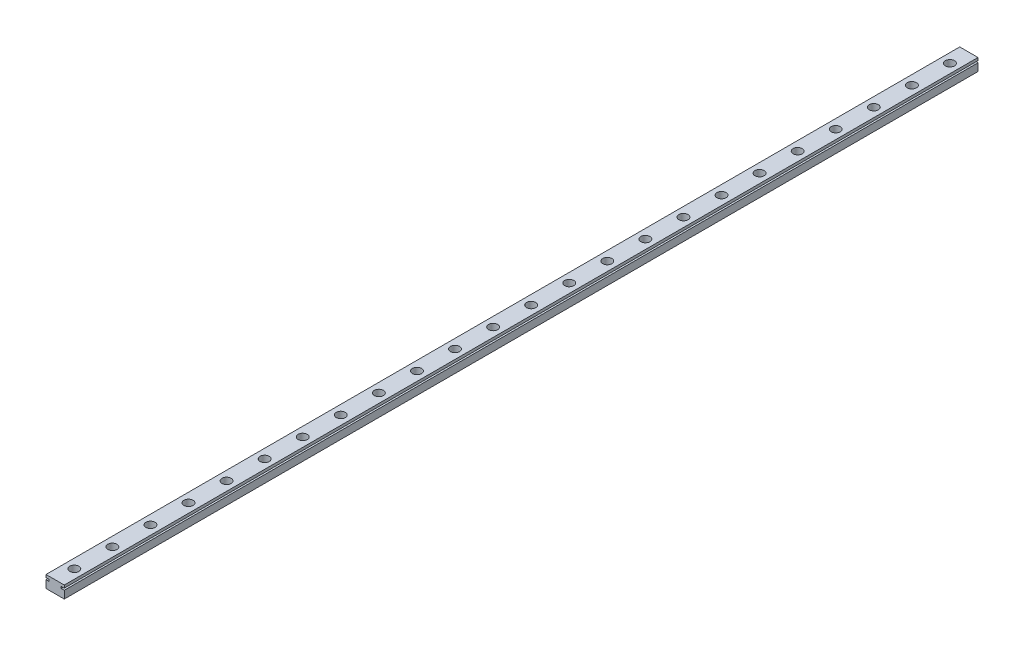
SolidWorks part; units mm, degrees
ref_plane "Plan de face" through (0, 0, 0) normal (0, 0, 1) x (1, 0, 0)
ref_plane "Plan de dessus" through (0, 0, 0) normal (0, 1, 0) x (1, 0, 0)
ref_plane "Plan de droite" through (0, 0, 0) normal (1, 0, 0) x (0, 0, -1)
sketch "Esquisse1" plane through (0, 0, 0) normal (0, 0, 1) x (1, 0, 0)
  line L0 (-2.288, -3.1489) -> (9.712, -3.1489)
  line L1 (9.712, -3.1489) -> (9.712, 1.8511)
  line L2 (9.712, 1.8511) -> (7.712, 1.8511)
  line L3 (7.712, 1.8511) -> (7.712, 3.0511)
  line L4 (7.712, 3.0511) -> (9.712, 3.0511)
  line L5 (9.712, 3.0511) -> (9.712, 4.8511)
  line L6 (9.712, 4.8511) -> (-2.288, 4.8511)
  line L7 (-2.288, 4.8511) -> (-2.288, 3.0511)
  line L8 (-2.288, 3.0511) -> (-0.288, 3.0511)
  line L9 (-0.288, 3.0511) -> (-0.288, 1.8511)
  line L10 (-0.288, 1.8511) -> (-2.288, 1.8511)
  line L11 (-2.288, 1.8511) -> (-2.288, -3.1489)
  dimension "D1" = 5
  dimension "D2" = 1.2
  dimension "D3" = 1.8
  dimension "D4" = 2
  dimension "D5" = 12
extrude "Boss.-Extru.1" add sketch "Esquisse1" along normal blind 600
sketch "Esquisse2" plane through (0, 4.8511, 0) normal (0, 1, 0) x (1, 0, 0)
  line L0 (9.712, -600) -> (-2.288, -600) construction
  circle A0 centre (3.7928, -587.5) radius 3
  circle A1 centre (3.7928, -562.5) radius 3
  circle A2 centre (3.7928, -537.5) radius 3
  circle A3 centre (3.7928, -512.5) radius 3
  circle A4 centre (3.7928, -487.5) radius 3
  circle A5 centre (3.7928, -462.5) radius 3
  circle A6 centre (3.7928, -437.5) radius 3
  circle A7 centre (3.7928, -412.5) radius 3
  circle A8 centre (3.7928, -387.5) radius 3
  circle A9 centre (3.7928, -362.5) radius 3
  circle A10 centre (3.7928, -337.5) radius 3
  circle A11 centre (3.7928, -312.5) radius 3
  circle A12 centre (3.7928, -287.5) radius 3
  circle A13 centre (3.7928, -262.5) radius 3
  circle A14 centre (3.7928, -237.5) radius 3
  circle A15 centre (3.7928, -212.5) radius 3
  circle A16 centre (3.7928, -187.5) radius 3
  circle A17 centre (3.7928, -162.5) radius 3
  circle A18 centre (3.7928, -137.5) radius 3
  circle A19 centre (3.7928, -112.5) radius 3
  circle A20 centre (3.7928, -87.5) radius 3
  circle A21 centre (3.7928, -62.5) radius 3
  circle A22 centre (3.7928, -37.5) radius 3
  circle A23 centre (3.7928, -12.5) radius 3
  dimension "D2" = 6
  dimension "D1" = 12.5
  dimension "D3" = 24
extrude "Enlèv. mat.-Extru.1" cut sketch "Esquisse2" against normal blind 4.5
sketch "Esquisse3" plane through (0, 0.3511, 0) normal (0, 1, 0) x (1, 0, 0)
  circle A0 centre (3.7928, -587.5) radius 1.75
  circle A1 centre (3.7928, -562.5) radius 1.75
  circle A2 centre (3.7928, -537.5) radius 1.75
  circle A3 centre (3.7928, -512.5) radius 1.75
  circle A4 centre (3.7928, -487.5) radius 1.75
  circle A5 centre (3.7928, -462.5) radius 1.75
  circle A6 centre (3.7928, -437.5) radius 1.75
  circle A7 centre (3.7928, -412.5) radius 1.75
  circle A8 centre (3.7928, -387.5) radius 1.75
  circle A9 centre (3.7928, -362.5) radius 1.75
  circle A10 centre (3.7928, -337.5) radius 1.75
  circle A11 centre (3.7928, -312.5) radius 1.75
  circle A12 centre (3.7928, -287.5) radius 1.75
  circle A13 centre (3.7928, -262.5) radius 1.75
  circle A14 centre (3.7928, -237.5) radius 1.75
  circle A15 centre (3.7928, -212.5) radius 1.75
  circle A16 centre (3.7928, -187.5) radius 1.75
  circle A17 centre (3.7928, -162.5) radius 1.75
  circle A18 centre (3.7928, -137.5) radius 1.75
  circle A19 centre (3.7928, -112.5) radius 1.75
  circle A20 centre (3.7928, -87.5) radius 1.75
  circle A21 centre (3.7928, -62.5) radius 1.75
  circle A22 centre (3.7928, -37.5) radius 1.75
  circle A23 centre (3.7928, -12.5) radius 1.75
  dimension "D1" = 3.5
  dimension "D2" = 24
extrude "Enlèv. mat.-Extru.2" cut sketch "Esquisse3" against normal up to next
sketch "Esquisse4" plane through (0, 0, 600) normal (0, 0, 1) x (1, 0, 0)
  line L0 (3.712, -3.1489) -> (3.712, 4.8511) construction
  line L1 (-2.288, -3.1489) -> (9.712, -3.1489) construction
  line L2 (9.712, 4.8511) -> (-2.288, 4.8511) construction
sketch "Esquisse5" plane through (0, 0, 0) normal (0, 0, -1) x (-1, 0, 0)
  line L0 (-3.712, 4.8511) -> (-3.712, -3.1489) construction
  line L1 (-9.712, 4.8511) -> (2.288, 4.8511) construction
  line L2 (2.288, -3.1489) -> (-9.712, -3.1489) construction
